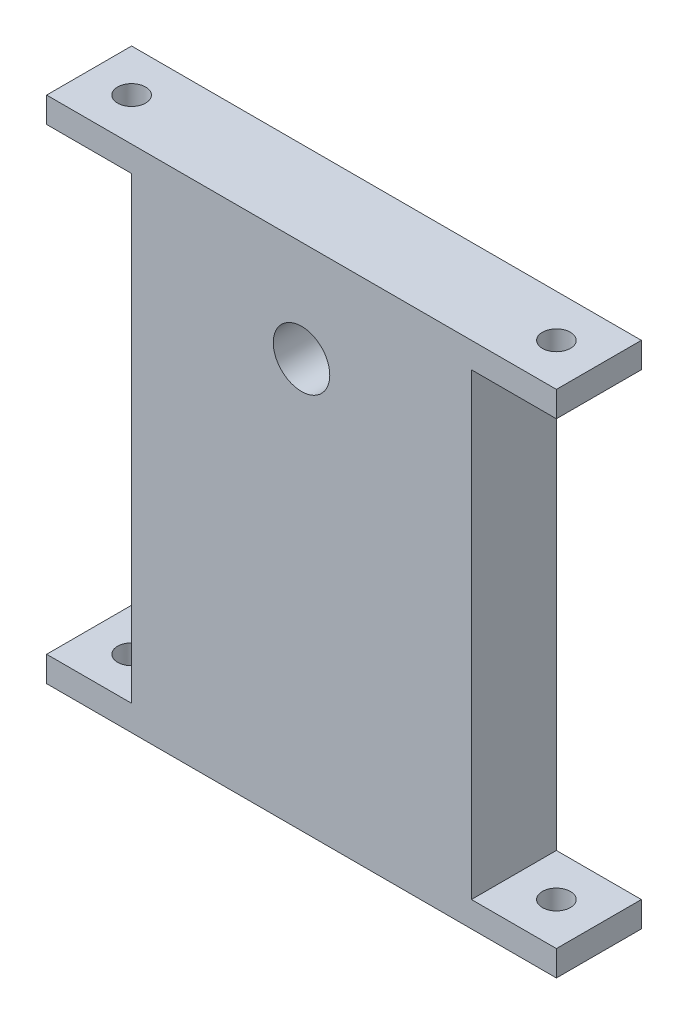
SolidWorks part; units mm, degrees
ref_plane "Front Plane" through (0, 0, 0) normal (0, 0, 1) x (1, 0, 0)
ref_plane "Top Plane" through (0, 0, 0) normal (0, 1, 0) x (1, 0, 0)
ref_plane "Right Plane" through (0, 0, 0) normal (1, 0, 0) x (0, 0, -1)
sketch "Sketch1" plane through (0, 0, 0) normal (0, 0, 1) x (1, 0, 0)
  line L1 (-20, 30) -> (20, 30)
  line L2 (-20, 30) -> (-20, -30)
  line L3 (-20, -30) -> (20, -30)
  line L4 (20, 30) -> (20, -30)
  circle A0 centre (0, 18.11) radius 3.325
  point P0 (0, 0)
  dimension "D4" = 6.65
  dimension "D1" = 40
  dimension "D2" = 60
  dimension "D3" = 48.11
  dimension "D5" = 30
  dimension "D6" = 20
extrude "Boss-Extrude1" add sketch "Sketch1" along normal blind 10
sketch "Esquisse1" plane through (20, 0, 0) normal (1, 0, 0) x (0, 0, -1)
  line L0 (0, 30) -> (-10, 30)
  line L1 (-10, 30) -> (-10, 27)
  line L2 (-10, -30) -> (-10, 30) construction
  line L3 (-10, 27) -> (0, 27)
  line L4 (0, -30) -> (0, 30) construction
  line L5 (0, 27) -> (0, 30)
  line L6 (0, -30) -> (0, -27)
  line L7 (0, -27) -> (-10, -27)
  line L8 (-10, -27) -> (-10, -30)
  line L9 (-10, -30) -> (0, -30)
  dimension "D1" = 3
  dimension "D2" = 3
extrude "Boss.-Extru.1" add sketch "Esquisse1" along normal blind 10
sketch "Esquisse2" plane through (-20, 0, 0) normal (-1, 0, 0) x (0, 0, 1)
  line L0 (0, 30) -> (10, 30)
  line L1 (10, 30) -> (10, 27)
  line L2 (10, 27) -> (0, 27)
  line L3 (0, 30) -> (0, -30) construction
  line L4 (0, 27) -> (0, 30)
  line L5 (10, 30) -> (10, -30) construction
  line L6 (0, -30) -> (10, -30)
  line L7 (0, -30) -> (0, -27)
  line L8 (0, -27) -> (10, -27)
  line L9 (10, -30) -> (10, -27)
  dimension "D1" = 3
  dimension "D2" = 3
extrude "Boss.-Extru.2" add sketch "Esquisse2" along normal blind 10
sketch "Esquisse3" plane through (0, 27, 0) normal (0, -1, 0) x (1, 0, 0)
  line L0 (0, -33) -> (0, 33) construction
  circle A0 centre (-25, 5) radius 1.65
  circle A1 centre (25, 5) radius 1.65
  dimension "D3" = 3.3
  dimension "D1" = 5
  dimension "D2" = 5
extrude "Enlèv. mat.-Extru.1" cut sketch "Esquisse3" against normal through all both and the other way through all
